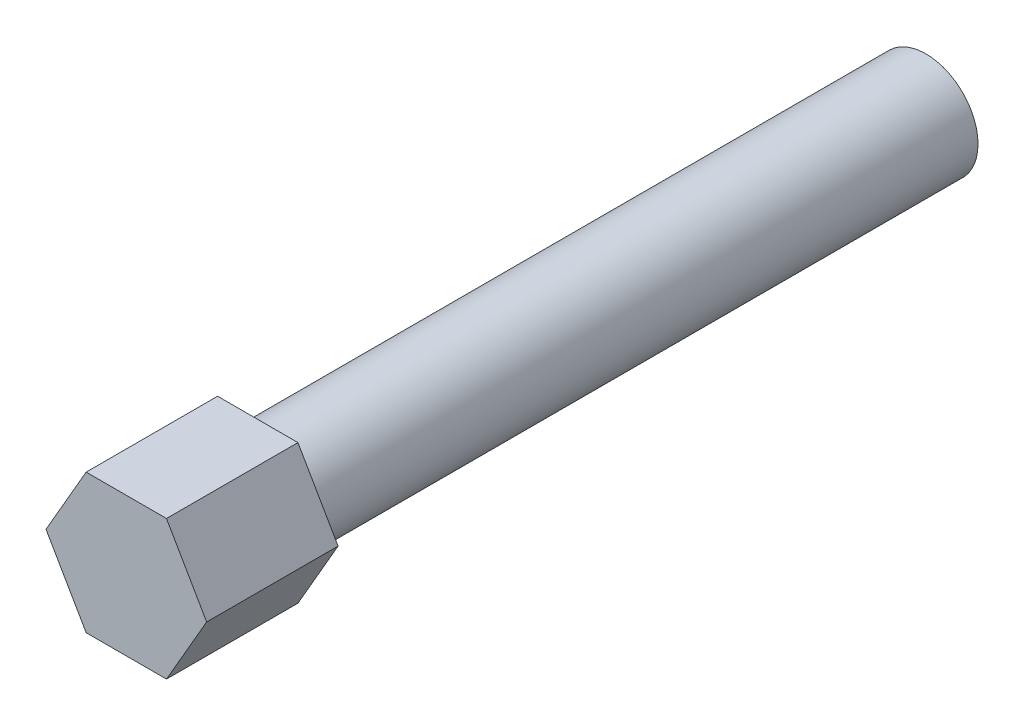
SolidWorks part; units mm, degrees
ref_plane "Front Plane" through (0, 0, 0) normal (0, 0, 1) x (1, 0, 0)
ref_plane "Top Plane" through (0, 0, 0) normal (0, 1, 0) x (1, 0, 0)
ref_plane "Right Plane" through (0, 0, 0) normal (1, 0, 0) x (0, 0, -1)
sketch "Sketch1" plane through (0, 0, 0) normal (0, 0, 1) x (1, 0, 0)
  line L1 (3.6662, -6.35) -> (7.3323, 0)
  line L2 (7.3323, 0) -> (3.6662, 6.35)
  line L3 (3.6662, 6.35) -> (-3.6662, 6.35)
  line L4 (-3.6662, 6.35) -> (-7.3323, 0)
  line L5 (-7.3323, 0) -> (-3.6662, -6.35)
  line L6 (-3.6662, -6.35) -> (3.6662, -6.35)
  circle A0 centre (0, 0) radius 6.35 construction
  dimension "D1" = 12.7
extrude "Boss-Extrude1" add sketch "Sketch1" along normal blind 12
sketch "Sketch2" plane through (0, 0, 0) normal (0, 0, -1) x (-1, 0, 0)
  circle A0 centre (0, 0) radius 4.75
  dimension "D1" = 9.5
extrude "Boss-Extrude2" add sketch "Sketch2" along normal blind 61
sketch "Sketch3" plane through (0, 0, -61) normal (0, 0, -1) x (-1, 0, 0)
  line L0 (-5, 3) -> (-2.6458, 3) construction
  line L1 (-2.6458, 3) -> (2.6458, 3)
  line L2 (-5, 3) -> (-5, -3) construction
  line L3 (-2.6458, -3) -> (2.6458, -3)
  line L4 (5, 3) -> (5, -3) construction
  line L5 (-5, 3) -> (5, -3) construction
  line L6 (-5, -3) -> (5, 3) construction
  line L7 (-5, -3) -> (-2.6458, -3) construction
  line L8 (2.6458, -3) -> (5, -3) construction
  line L9 (2.6458, 3) -> (5, 3) construction
  arc A0 (-2.6458, 3) -> (-2.6458, -3) centre (0, 0) ccw
  arc A1 (2.6458, 3) -> (-2.6458, 3) centre (0, 0) ccw construction
  arc A2 (-2.6458, -3) -> (2.6458, -3) centre (0, 0) ccw construction
  arc A3 (2.6458, -3) -> (2.6458, 3) centre (0, 0) ccw
  point P0 (0, 0)
  dimension "D1" = 8
  dimension "D2" = 6
  dimension "D3" = 10
extrude "Cut-Extrude1" cut sketch "Sketch3" against normal blind 14
